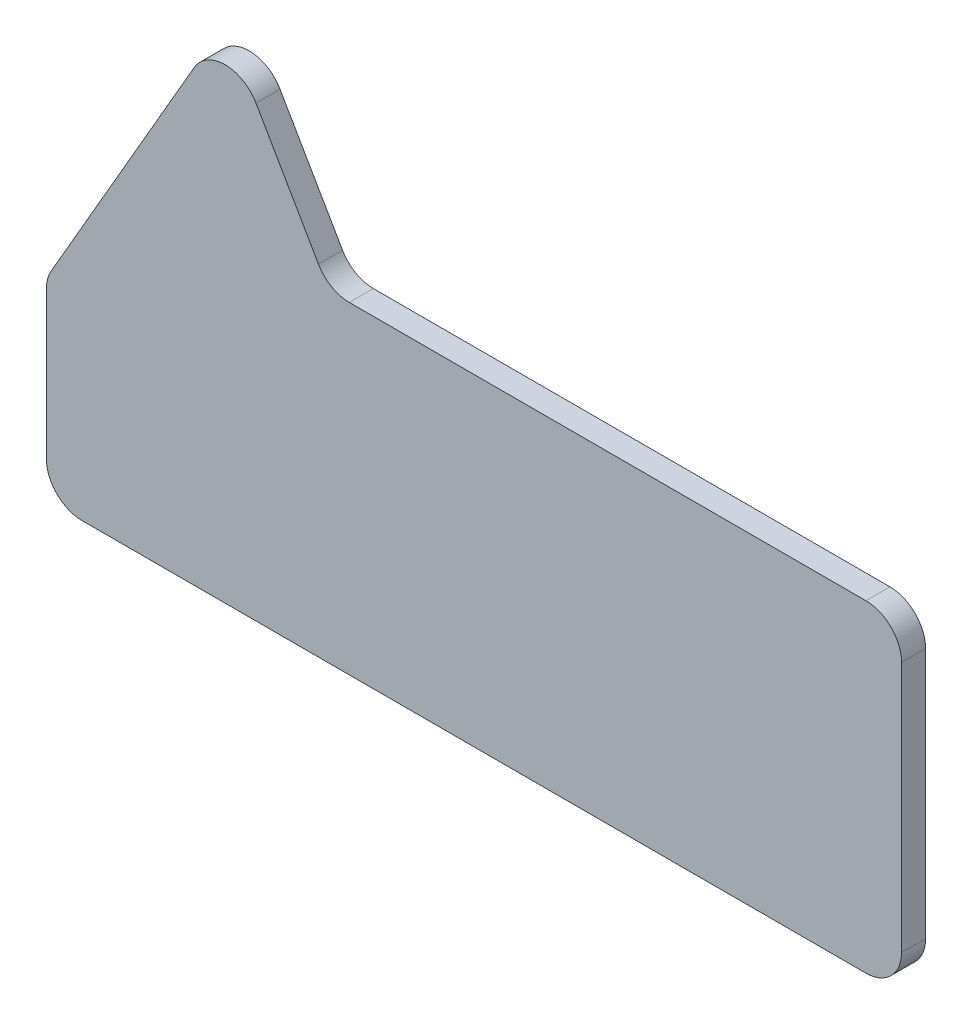
SolidWorks part; units mm, degrees
ref_plane "Front Plane" through (0, 0, 0) normal (0, 0, 1) x (1, 0, 0)
ref_plane "Top Plane" through (0, 0, 0) normal (0, 1, 0) x (1, 0, 0)
ref_plane "Right Plane" through (0, 0, 0) normal (1, 0, 0) x (0, 0, -1)
sketch "Sketch1" plane through (0, 0, 0) normal (0, 0, 1) x (1, 0, 0)
  line L0 (-14.2521, 14.5731) -> (-22.2822, 0.6645)
  line L6 (-12.395, 13.7896) -> (-12.645, 13.3566) construction
  line L7 (-12.6932, 13.6731) -> (-12.3468, 13.4731) construction
  line L8 (23.4387, 7.5037) -> (-5.5518, 7.5037)
  line L9 (-7.2838, 8.5037) -> (-10.788, 14.5731)
  line L10 (-12.4718, 13.2566) -> (-12.2218, 13.6896)
  line L11 (-12.2218, 13.6896) -> (-12.5682, 13.8896)
  line L12 (-12.5682, 13.8896) -> (-12.8182, 13.4566)
  line L13 (-12.8182, 13.4566) -> (-12.4718, 13.2566)
  line L14 (-12.4718, 13.2566) -> (-12.2218, 13.6896) construction
  line L15 (-12.2218, 13.6896) -> (-12.5682, 13.8896) construction
  line L16 (-12.5682, 13.8896) -> (-12.8182, 13.4566) construction
  line L17 (-12.8182, 13.4566) -> (-12.4718, 13.2566) construction
  line L18 (-20.5502, -10.5963) -> (23.4387, -10.5963)
  line L20 (25.4387, 5.5037) -> (25.4387, -8.5963)
  line L21 (-22.5502, -8.5963) -> (-22.5502, -0.3355)
  line L22 (-23.0502, 1.9325) -> (-23.0502, -1.3206) construction
  line L23 (-21.5502, -10.8463) -> (24.4387, -10.8463) construction
  line L24 (25.9387, -1.3206) -> (25.9387, 14.4056) construction
  circle A0 centre (-12.52, 13.5731) radius 0.6 construction
  circle A1 centre (-12.52, 13.5731) radius 1.5 construction
  arc A2 (-10.788, 14.5731) -> (-14.2521, 14.5731) centre (-12.52, 13.5731) ccw construction
  arc A8 (25.4387, 5.5037) -> (23.4387, 7.5037) centre (23.4387, 5.5037) ccw
  arc A10 (-20.5502, -10.5963) -> (-22.5502, -8.5963) centre (-20.5502, -8.5963) cw
  arc A12 (23.4387, -10.5963) -> (25.4387, -8.5963) centre (23.4387, -8.5963) ccw
  arc A13 (-7.2838, 8.5037) -> (-5.5518, 7.5037) centre (-5.5518, 9.5037) ccw
  arc A14 (-14.2521, 14.5731) -> (-10.788, 14.5731) centre (-12.52, 13.5731) cw
  arc A15 (-22.2822, 0.6645) -> (-22.5502, -0.3355) centre (-20.5502, -0.3355) ccw
  point P0 (0, 0)
  point P37 (0, 0)
  dimension "D2" = 1.2
  dimension "D4" = 3
  dimension "D5" = 4
  dimension "D6" = 0.5
  dimension "D9" = 2
  dimension "D11" = 2
  dimension "D7" = 2
  dimension "D12" = 14.1
  dimension "D13" = 0.5
  dimension "D14" = 2
  dimension "D15" = 2
  dimension "D1" = 0
  dimension "D3" = 0.25
  dimension "D8" = 120
  dimension "D10" = 150
extrude "Boss-Extrude1" add sketch "Sketch1" along normal blind 1.35
